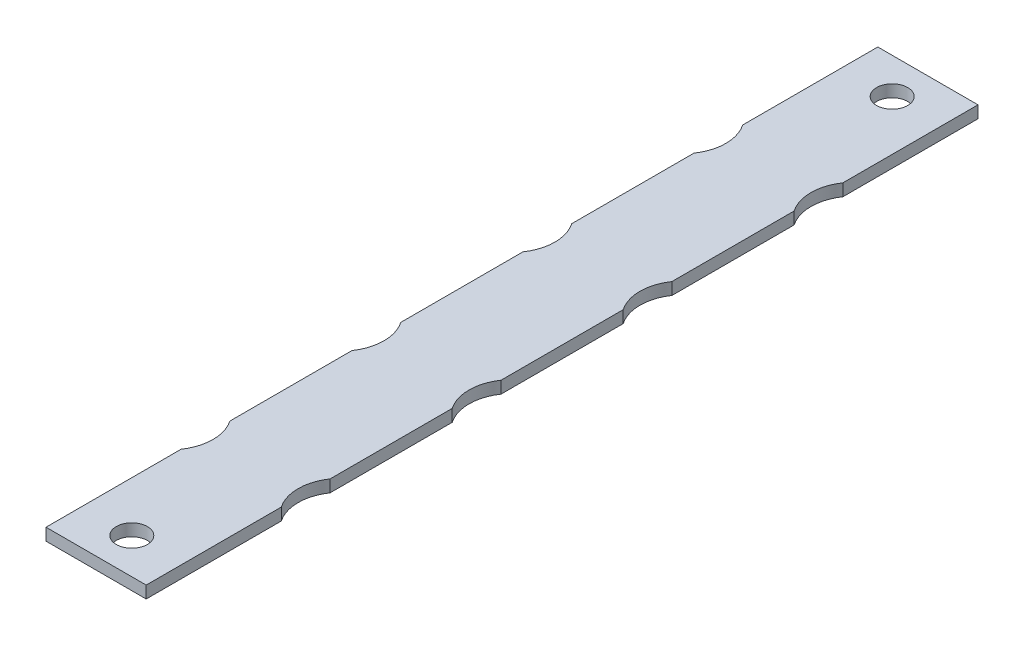
SolidWorks part; units mm, degrees
material "1100-H12 Rod (SS)"
ref_plane "X-Y Datum" through (0, 0, 0) normal (0, 0, 1) x (1, 0, 0)
ref_plane "X-Z Datum" through (0, 0, 0) normal (0, 1, 0) x (1, 0, 0)
ref_plane "Y-Z Datum" through (0, 0, 0) normal (1, 0, 0) x (0, 0, -1)
sketch "Sketch1" plane through (0, 0, 0) normal (0, 1, 0) x (1, 0, 0)
  line L1 (0, 0) -> (13.25, 0)
  line L2 (0, 0) -> (0, 110.0016)
  line L3 (0, 110.0016) -> (13.25, 110.0016)
  line L4 (13.25, 0) -> (13.25, 110.0016)
extrude "Boss-Extrude1" add sketch "Sketch1" along normal blind 1.6002 contours L3 L4 L1 L2
sketch "Sketch2" plane through (0, 1.6002, 0) normal (0, 1, 0) x (1, 0, 0)
  line L0 (6.625, 0) -> (6.625, 4.7244) construction
  line L1 (0, 0) -> (13.25, 0) construction
  line L2 (6.625, 110.0016) -> (6.625, 105.2772) construction
  line L3 (0, 110.0016) -> (13.25, 110.0016) construction
  circle A0 centre (6.625, 4.7244) radius 2.0574
  circle A1 centre (6.625, 105.2772) radius 2.0574
extrude "Cut-Extrude1" cut sketch "Sketch2" against normal through all
sketch "Sketch3" plane through (0, 1.6002, 0) normal (0, 1, 0) x (1, 0, 0)
  line L0 (0, 110.0016) -> (0, 88.9098) construction
  line L1 (0, 0) -> (0, 110.0016) construction
  line L2 (0, 88.9098) -> (-4.7, 88.9098) construction
  line L3 (0, 88.9098) -> (1, 88.9098) construction
  line L4 (6.625, 110.0016) -> (6.625, 0) construction
  line L5 (0, 110.0016) -> (13.25, 110.0016) construction
  line L6 (0, 0) -> (13.25, 0) construction
  circle A0 centre (-4.7, 88.9098) radius 5.7
  circle A1 centre (-4.7, 66.3038) radius 5.7
  circle A2 centre (-4.7, 43.6978) radius 5.7
  circle A3 centre (-4.7, 21.0918) radius 5.7
  circle A4 centre (17.95, 21.0918) radius 5.7
  circle A5 centre (17.95, 43.6978) radius 5.7
  circle A6 centre (17.95, 66.3038) radius 5.7
  circle A7 centre (17.95, 88.9098) radius 5.7
  dimension "D1" = 4
extrude "Cut-Extrude2" cut sketch "Sketch3" against normal through all
